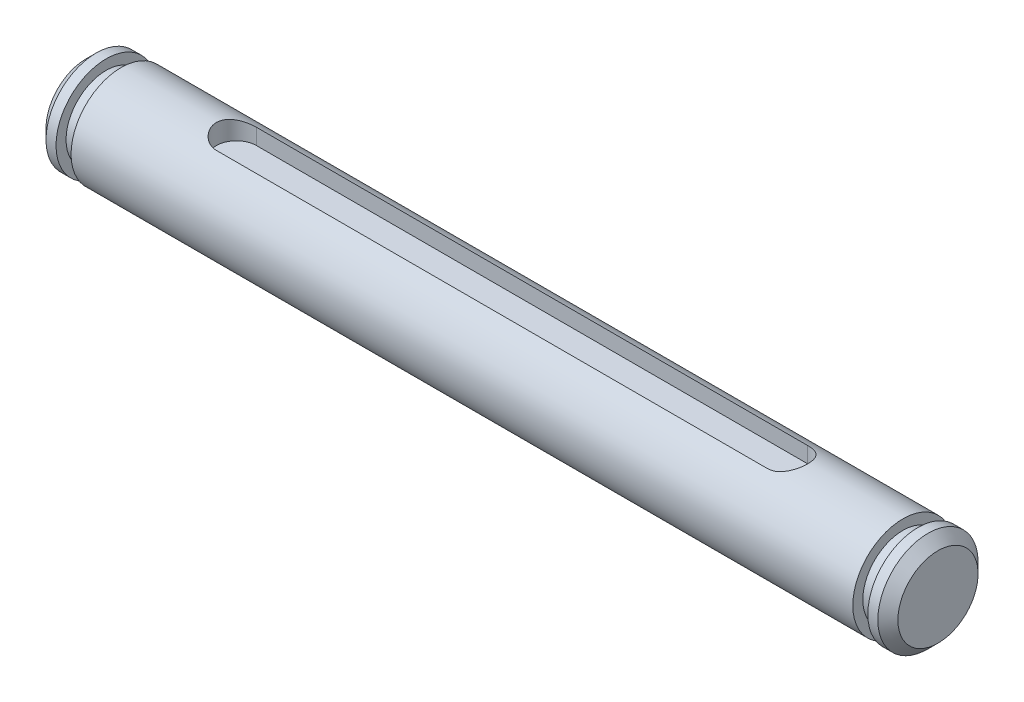
SolidWorks part; units mm, degrees
material "Plain Carbon Steel"
ref_plane "Front Plane" through (0, 0, 0) normal (0, 0, 1) x (1, 0, 0)
ref_plane "Top Plane" through (0, 0, 0) normal (0, 1, 0) x (1, 0, 0)
ref_plane "Right Plane" through (0, 0, 0) normal (1, 0, 0) x (0, 0, -1)
sketch "Sketch1" plane through (0, 0, 0) normal (0, 0, 1) x (1, 0, 0)
  line L0 (-42.5, 0) -> (-42.5, 5)
  line L1 (-42.5, 0) -> (42.5, 0)
  line L2 (-42.5, 5) -> (-40.5, 5)
  line L3 (-40.5, 5) -> (-40.5, 4)
  line L4 (-40.5, 4) -> (-39, 4)
  line L5 (-39, 4) -> (-39, 5)
  line L6 (-39, 5) -> (39, 5)
  line L7 (-47.152, 0) -> (-42.5, 0) construction
  line L8 (0, 5) -> (0, 0) construction
  line L9 (39, 4) -> (39, 5)
  line L10 (40.5, 4) -> (39, 4)
  line L11 (40.5, 5) -> (40.5, 4)
  line L12 (42.5, 5) -> (40.5, 5)
  line L13 (42.5, 0) -> (42.5, 5)
  dimension "D1" = 10
  dimension "D2" = 78
  dimension "D3" = 1.5
  dimension "D4" = 8
  dimension "D5" = 2
revolve "Revolve1" add sketch "Sketch1" angle 360 about L7
chamfer "Chamfer1" distance 1 angle 45 2 edges at (42.5, 0, 5) (-42.5, 0, 5)
sketch "Sketch3" plane through (0, 0, 0) normal (1, 0, 0) x (0, 0, -1)
  line L0 (2, 7) -> (2, 3)
  line L1 (2, 7) -> (-2, 7)
  line L2 (2, 3) -> (-2, 3)
  line L3 (-2, 7) -> (-2, 3)
  line L4 (2, 7) -> (-2, 3) construction
  line L5 (2, 3) -> (-2, 7) construction
  line L6 (0, 5) -> (0, 0) construction
  circle A0 centre (0, 0) radius 5 construction
  point P1 (0, 5)
  dimension "D1" = 4
  dimension "D2" = 4
extrude "Cut-Extrude1" cut sketch "Sketch3" against normal blind 5
sketch "Sketch4" plane through (0, 3, 0) normal (0, 1, 0) x (1, 0, 0)
  line L0 (27.5, 0) -> (-27.5, 0) construction
  line L1 (0, -2) -> (0, 2) construction
  line L2 (27.5, -2) -> (0, -2)
  line L3 (27.5, 2) -> (0, 2)
  line L4 (-5, 2) -> (0, 2) construction
  line L7 (0, 0) -> (0, -8.0271) construction
  line L8 (0, 2) -> (-27.5, 2)
  line L9 (0, -2) -> (-27.5, -2)
  line L10 (-5, -2) -> (0, -2) construction
  arc A0 (27.5, -2) -> (27.5, 2) centre (27.5, 0) ccw
  arc A1 (-27.5, 2) -> (-27.5, -2) centre (-27.5, 0) ccw
  point P4 (0, 0)
  dimension "D1" = 55
extrude "Cut-Extrude2" cut sketch "Sketch4" along normal blind 10
